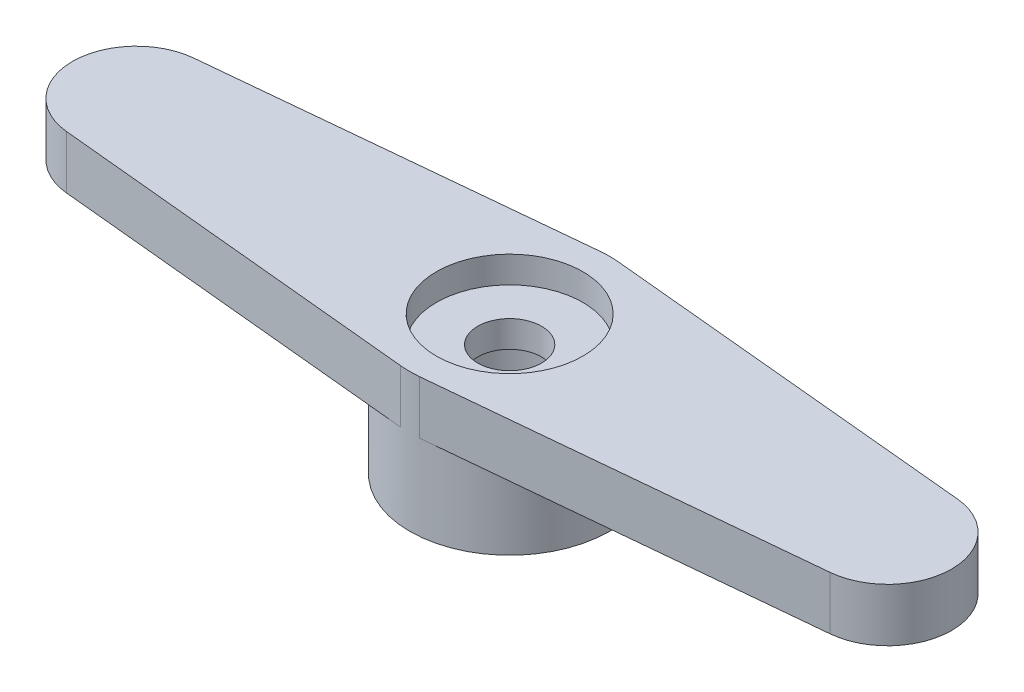
SolidWorks part; units mm, degrees
ref_plane "Front Plane" through (0, 0, 0) normal (0, 0, 1) x (1, 0, 0)
ref_plane "Top Plane" through (0, 0, 0) normal (0, 1, 0) x (1, 0, 0)
ref_plane "Right Plane" through (0, 0, 0) normal (1, 0, 0) x (0, 0, -1)
sketch "Sketch1" plane through (0, 0, 0) normal (0, 1, 0) x (1, 0, 0)
  line L0 (0, 0) -> (14.2, 0) construction
  line L1 (0.3565, 3.733) -> (14.4282, 2.3891)
  line L2 (0.3565, -3.733) -> (14.4282, -2.3891)
  line L3 (0, 0) -> (-14.0236, 0) construction
  line L4 (-0.361, -3.7326) -> (-14.2546, -2.3889)
  line L5 (-14.2546, 2.3889) -> (-0.361, 3.7326)
  arc A0 (0.3565, 3.733) -> (-0.361, 3.7326) centre (0, 0) ccw
  arc A1 (14.4282, -2.3891) -> (14.4282, 2.3891) centre (14.2, 0) ccw
  circle A2 centre (0, 0) radius 1.2
  arc A3 (-14.2546, 2.3889) -> (-14.2546, -2.3889) centre (-14.0236, 0) ccw
  arc A4 (-0.361, -3.7326) -> (0.3565, -3.733) centre (0, 0) ccw
  dimension "D1" = 7.5
  dimension "D3" = 4.8
  dimension "D4" = 2.4
  dimension "D5" = 4.8
  dimension "D2" = 14.2
extrude "Boss-Extrude1" add sketch "Sketch1" along normal blind 2
sketch "Sketch2" plane through (0, 0, 0) normal (0, -1, 0) x (1, 0, 0)
  line L2 (14.4282, 2.3891) -> (0.3565, 3.733)
  line L3 (0.3565, -3.733) -> (14.4282, -2.3891)
  line L4 (14.4282, 2.3891) -> (0.3565, 3.733)
  line L5 (0.3565, -3.733) -> (14.4282, -2.3891)
  line L8 (-0.361, 3.7326) -> (-14.2546, 2.3889)
  line L9 (-0.361, 3.7326) -> (-14.2546, 2.3889)
  line L10 (-14.2546, -2.3889) -> (-0.361, -3.7326)
  line L11 (-14.2546, -2.3889) -> (-0.361, -3.7326)
  circle A0 centre (0, 0) radius 3.75
  circle A1 centre (0, 0) radius 1.2
  arc A2 (14.4282, -2.3891) -> (14.4282, 2.3891) centre (14.2, 0) ccw
  arc A3 (-0.361, -3.7326) -> (0.3565, -3.733) centre (0, 0) ccw
  arc A4 (14.4282, -2.3891) -> (14.4282, 2.3891) centre (14.2, 0) ccw
  arc A9 (0.3565, 3.733) -> (-0.361, 3.7326) centre (0, 0) ccw
  arc A10 (0.3565, 3.733) -> (-0.361, 3.7326) centre (0, 0) ccw
  arc A11 (-14.2546, 2.3889) -> (-14.2546, -2.3889) centre (-14.0236, 0) ccw
  arc A12 (-14.2546, 2.3889) -> (-14.2546, -2.3889) centre (-14.0236, 0) ccw
  arc M7 (-0.361, -3.7326) -> (0.3565, -3.733) centre (0, 0) ccw
  circle M9 centre (0, 0) radius 1.2
  dimension "D1" = 0
extrude "Boss-Extrude2" add sketch "Sketch2" along normal blind 3.2 contours A0 M7 M9
sketch "Sketch3" plane through (0, -3.2, 0) normal (0, -1, 0) x (1, 0, 0)
  circle A0 centre (0, 0) radius 2.4
  dimension "D1" = 4.8
extrude "Cut-Extrude3" cut sketch "Sketch3" against normal up to surface (3.2 mm away) up to face at (8.7837, 0, 0)
sketch "Sketch4" plane through (0, 2, 0) normal (0, 1, 0) x (1, 0, 0)
  circle A0 centre (0, 0) radius 2.75
  dimension "D1" = 5.5
extrude "Cut-Extrude4" cut sketch "Sketch4" against normal blind 1
